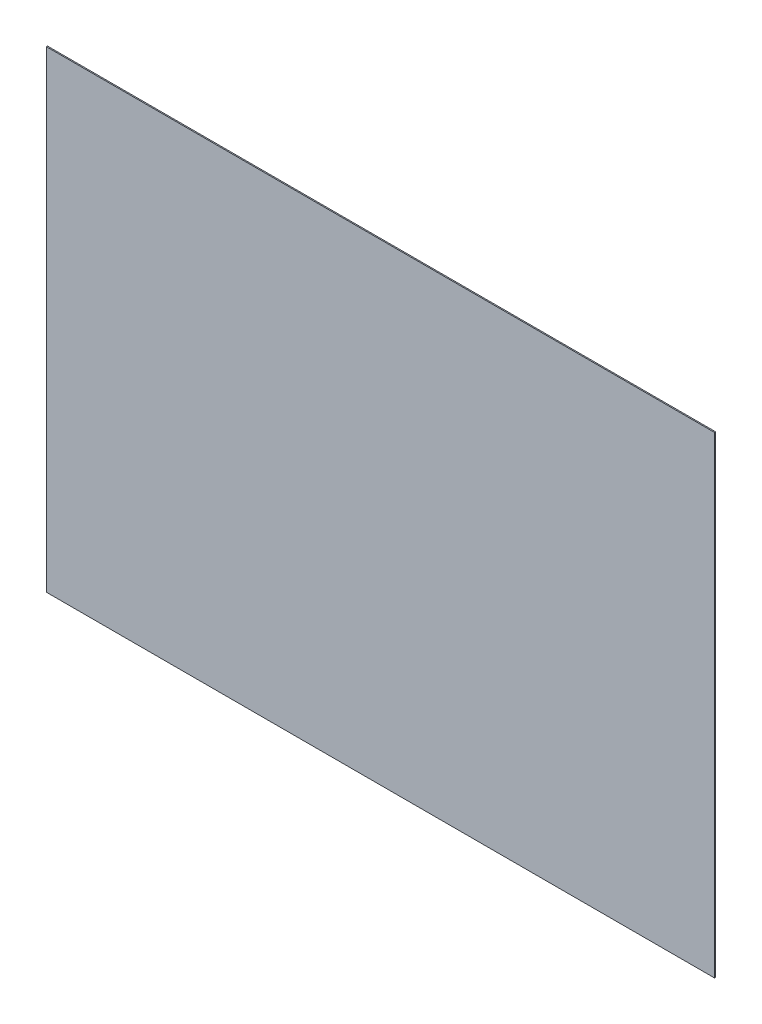
SolidWorks part; units mm, degrees
ref_plane "Alzado" through (0, 0, 0) normal (0, 0, 1) x (1, 0, 0)
ref_plane "Planta" through (0, 0, 0) normal (0, 1, 0) x (1, 0, 0)
ref_plane "Vista lateral" through (0, 0, 0) normal (1, 0, 0) x (0, 0, -1)
sketch "Croquis1" plane through (0, 0, 0) normal (0, 0, 1) x (1, 0, 0)
  line L1 (0, 0) -> (297, 0)
  line L2 (0, 0) -> (0, 210)
  line L3 (0, 210) -> (297, 210)
  line L4 (297, 0) -> (297, 210)
  dimension "D1" = 297
  dimension "D2" = 210
extrude "Saliente-Extruir1" add sketch "Croquis1" along normal blind 0.5
